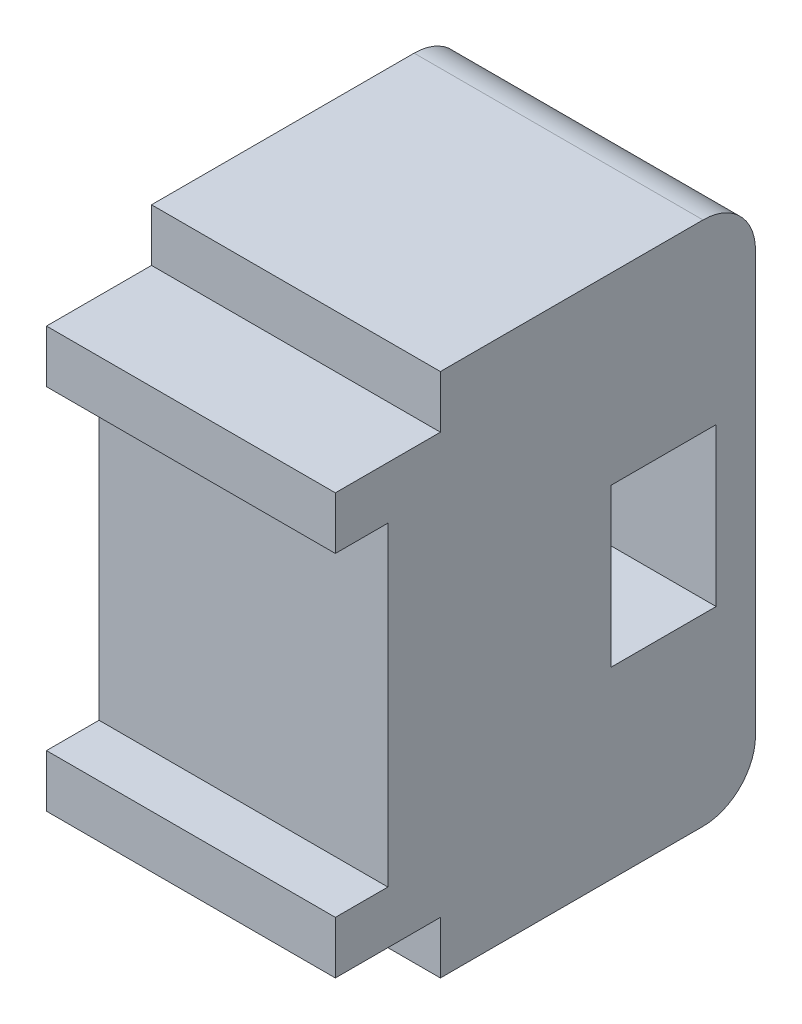
SolidWorks part; units mm, degrees
ref_plane "Front Plane" through (0, 0, 0) normal (1, 0, 0) x (0, 1, 0)
ref_plane "Top Plane" through (0, 0, 0) normal (0, 0, 1) x (0, 1, 0)
ref_plane "Right Plane" through (0, 0, 0) normal (0, 1, 0) x (-1, 0, 0)
sketch "Sketch1" plane through (0, 0, 0) normal (1, 0, 0) x (0, 1, 0)
  line L1 (-10, 6) -> (10, 6)
  line L2 (-10, 6) -> (-10, -6)
  line L3 (-10, -6) -> (10, -6)
  line L4 (10, 6) -> (10, -6)
  line L5 (-10, 6) -> (10, -6) construction
  line L6 (-10, -6) -> (10, 6) construction
  point P0 (0, 0)
  dimension "D1" = 12
  dimension "D2" = 20
extrude "Boss-Extrude1" add sketch "Sketch1" along normal blind 11
sketch "Sketch5" plane through (0, 0, 0) normal (0, 0, 1) x (0, 1, 0)
  line L0 (10, 0) -> (-10, 0) construction
  line L1 (-8, 0) -> (8, 0)
  line L2 (-8, 0) -> (-8, -11)
  line L3 (-8, -11) -> (8, -11)
  line L4 (8, 0) -> (8, -11)
  line L5 (-10, -11) -> (-10, 0) construction
  line L6 (10, -11) -> (10, 0) construction
  line L7 (10, -11) -> (-10, -11) construction
  dimension "D1" = 2
  dimension "D2" = 2
  dimension "D3" = 0
extrude "Boss-Extrude2" add sketch "Sketch5" along normal blind 8
fillet "Fillet1" radius 2 2 edges at (5.5, 10, -6) (5.5, -10, -6)
sketch "Sketch7" plane through (0, 0, 0) normal (1, 0, 0) x (0, 1, 0)
  line L0 (-3, -4.5) -> (3, -4.5)
  line L1 (0, 0) -> (0, -0.5) construction
  line L2 (-3, -0.5) -> (3, -0.5)
  line L3 (-3, -0.5) -> (-3, -4.5)
  line L5 (3, -0.5) -> (3, -4.5)
  line L6 (-8, -6) -> (8, -6) construction
  dimension "D1" = 4
  dimension "D2" = 6
  dimension "D3" = 1.5
  dimension "D4" = 4
extrude "Cut-Extrude1" cut sketch "Sketch7" along normal blind 15
sketch "Sketch9" plane through (0, 0, 8) normal (0, 0, 1) x (1, 0, 0)
  line L0 (0, -8) -> (11, -8) construction
  line L1 (0, 8) -> (11, 8)
  line L2 (0, 8) -> (0, 6)
  line L3 (0, -8) -> (11, -8)
  line L4 (11, 8) -> (11, 6)
  line L5 (0, -8) -> (11, -8) construction
  line L6 (0, 6) -> (11, 6)
  line L7 (0, -6) -> (0, -8)
  line L8 (0, -6) -> (11, -6)
  line L9 (11, -6) -> (11, -8)
  dimension "D1" = 2
  dimension "D2" = 2
  dimension "D3" = 11
extrude "Boss-Extrude4" add sketch "Sketch9" along normal blind 2
